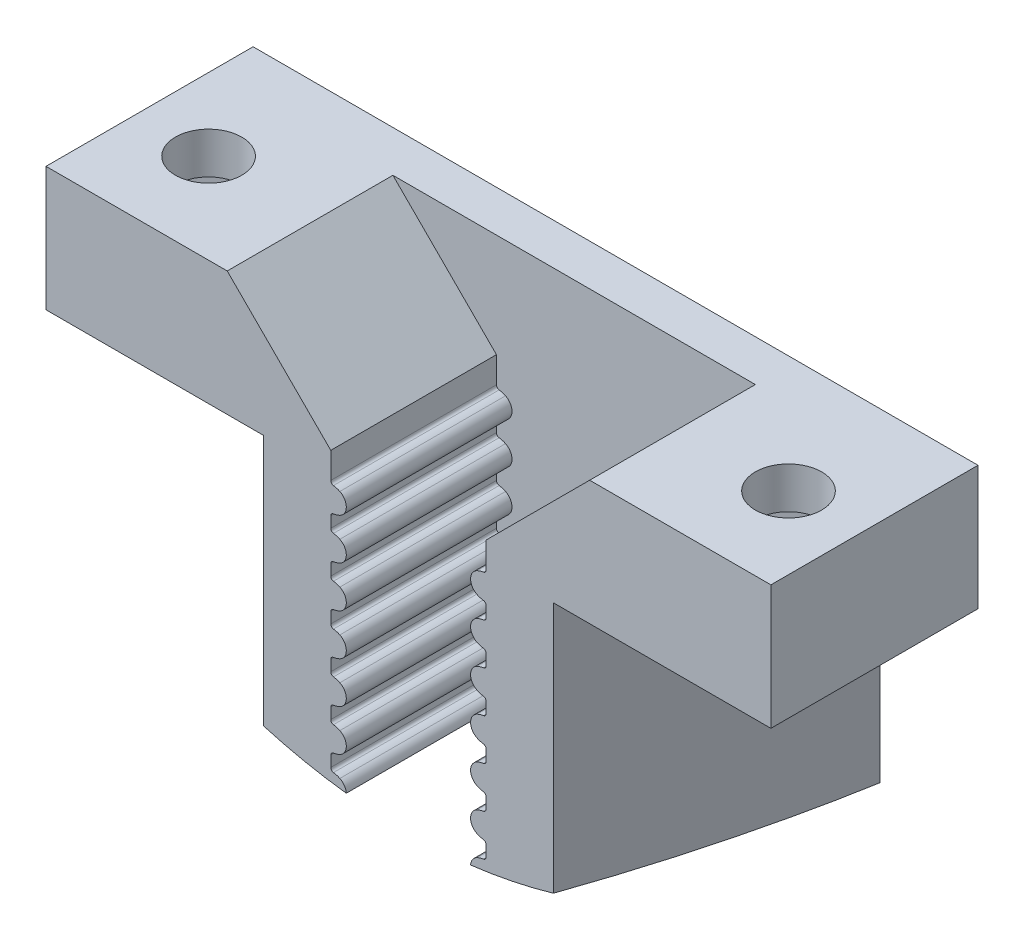
SolidWorks part; units mm, degrees
ref_plane "Front" through (0, 0, 0) normal (0, 0, 1) x (1, 0, 0)
ref_plane "Top" through (0, 0, 0) normal (0, 1, 0) x (1, 0, 0)
ref_plane "Right" through (0, 0, 0) normal (1, 0, 0) x (0, 0, -1)
sketch "Sketch1" plane through (0, 0, 0) normal (0, 0, 1) x (1, 0, 0)
  line L1 (-17.5, -3) -> (17.5, -3)
  line L2 (-17.5, -3) -> (-17.5, 3)
  line L3 (-17.5, 3) -> (17.5, 3)
  line L4 (17.5, -3) -> (17.5, 3)
  line L5 (-17.5, -3) -> (17.5, 3) construction
  line L6 (-17.5, 3) -> (17.5, -3) construction
  point P0 (0, 0)
  dimension "D1" = 35
  dimension "D2" = 6
extrude "Boss-Extrude1" add sketch "Sketch1" along normal blind 10
sketch "Sketch2" plane through (0, 0, 10) normal (0, 0, 1) x (1, 0, 0)
  line L0 (-17.5, -3) -> (17.5, -3) construction
  line L1 (-17.5, -3) -> (17.5, -3)
  arc A0 (-17.5, -3) -> (17.5, -3) centre (0, 14.8536) ccw
  dimension "D1" = 50
extrude "Boss-Extrude2" add sketch "Sketch2" against normal blind 10
sketch "Sketch4" plane through (0, 0, 10) normal (0, 0, 1) x (1, 0, 0)
  line L0 (17.5, 3) -> (-17.5, 3) construction
  line L1 (-3, 3) -> (3, 3)
  line L2 (-3, 3) -> (-3, -10.1464)
  line L3 (-3, -10.1464) -> (3, -10.1464)
  line L4 (3, 3) -> (3, -10.1464)
  arc A0 (-17.5, -3) -> (17.5, -3) centre (0, 14.8536) ccw construction
  point P10 (0, 3)
  dimension "D1" = 6
extrude "Cut-Extrude1" cut sketch "Sketch4" against normal blind 8
sketch "Sketch5" plane through (0, 0, 10) normal (0, 0, 1) x (1, 0, 0)
  line L0 (3, 2) -> (3.75, 2) construction
  line L1 (3, 4) -> (3.75, 4) construction
  line L2 (3, -9.9658) -> (3, 3) construction
  line L3 (3.75, 2.7402) -> (3, 2.7402) construction
  line L4 (3.75, 2.7402) -> (3.75, 2) construction
  line L5 (3.75, 3.2598) -> (3.75, 4) construction
  line L6 (3, 2) -> (3, 4)
  line L7 (17.5, 3) -> (3, 3) construction
  line L8 (3, -9.9658) -> (3, 3) construction
  line L9 (3.75, 3.2598) -> (3.75, 2.7402)
  arc A0 (3.3118, 2.4989) -> (3, 2) centre (3.555, 2) ccw
  arc A1 (3.6196, 2.5915) -> (3.3118, 2.4989) centre (3.75, 1.6) ccw
  arc A2 (3.6196, 2.5915) -> (3.75, 2.7402) centre (3.6, 2.7402) ccw
  arc A3 (3.3118, 3.5011) -> (3, 4) centre (3.555, 4) cw
  arc A4 (3.6196, 3.4085) -> (3.3118, 3.5011) centre (3.75, 4.4) cw
  arc A5 (3.6196, 3.4085) -> (3.75, 3.2598) centre (3.6, 3.2598) cw
  point P6 (3, 2)
  dimension "D4" = 1.11
  dimension "D7" = 0.3
  dimension "D8" = 1
  dimension "D1" = 0.6196
  dimension "D2" = 0.75
  dimension "D3" = 1
  dimension "D6" = 0.4
extrude "Cut-Extrude2" cut sketch "Sketch5" against normal blind 8
pattern_linear "LPattern2" count 10 spacing 2 along (0, -1, 0) of "Cut-Extrude2"
mirror "Mirror1" about plane through (0, 0, 0) normal (1, 0, 0) of "LPattern2", "Cut-Extrude2"
sketch "Sketch6" plane through (0, 3, 0) normal (0, 1, 0) x (1, 0, 0)
  line L0 (-17.5, 0) -> (-12.7735, 0)
  line L1 (17.5, 0) -> (-17.5, 0) construction
  line L2 (-12.7735, 0) -> (-7, -10)
  line L3 (-3.75, -10) -> (-17.5, -10) construction
  line L4 (-7, -10) -> (-17.5, -10)
  line L5 (-17.5, -10) -> (-17.5, 0)
  dimension "D1" = 60
  dimension "D2" = 10.5
extrude "Cut-Extrude3" cut sketch "Sketch6" against normal through all
mirror "Mirror2" about plane through (0, 0, 0) normal (1, 0, 0) of "Cut-Extrude3"
sketch "Sketch7" plane through (0, 3, 0) normal (0, 1, 0) x (1, 0, 0)
  line L0 (12.7735, 0) -> (-12.7735, 0) construction
  line L3 (-17.5, 0) -> (17.5, 0)
  line L4 (-17.5, 0) -> (-17.5, -10)
  line L5 (-17.5, -10) -> (17.5, -10)
  line L6 (17.5, 0) -> (17.5, -10)
  line L7 (-3.75, -10) -> (-7, -10) construction
  point P9 (0, 0)
  dimension "D1" = 35
extrude "Boss-Extrude3" add sketch "Sketch7" along normal blind 6
sketch "Sketch8" plane through (0, 0, 10) normal (0, 0, 1) x (1, 0, 0)
  line L0 (-17.5, 9) -> (17.5, 9) construction
  line L1 (-3.75, 3) -> (3.75, 3)
  line L2 (-3.75, 3) -> (-3.75, 9)
  line L3 (-3.75, 9) -> (3.75, 9)
  line L4 (3.75, 3) -> (3.75, 9)
extrude "Cut-Extrude4" cut sketch "Sketch8" against normal blind 8
sketch "Sketch9" plane through (0, 3, 0) normal (0, -1, 0) x (1, 0, 0)
  line L0 (7, 10) -> (17.5, 10) construction
  line L1 (16.8146, 4.025) -> (16.8146, 7.275)
  line L2 (16.8146, 7.275) -> (14, 8.9)
  line L3 (14, 8.9) -> (11.1854, 7.275)
  line L4 (11.1854, 7.275) -> (11.1854, 4.025)
  line L5 (11.1854, 4.025) -> (14, 2.4)
  line L6 (14, 2.4) -> (16.8146, 4.025)
  circle A0 centre (14, 5.65) radius 3.25 construction
  dimension "D1" = 6.5
  dimension "D2" = 4.35
  dimension "D3" = 14
extrude "Cut-Extrude5" cut sketch "Sketch9" against normal blind 4
mirror "Mirror3" about plane through (0, 0, 0) normal (1, 0, 0) of "Cut-Extrude5"
sketch "Sketch10" plane through (0, 7, 0) normal (0, -1, 0) x (1, 0, 0)
  circle A0 centre (14, 5.65) radius 1.6
  dimension "D1" = 3.2
extrude "Cut-Extrude6" cut sketch "Sketch10" against normal through all
mirror "Mirror4" about plane through (0, 0, 0) normal (1, 0, 0) of "Cut-Extrude6"
chamfer "Chamfer1" distance 5 angle 45 1 edges at (3.75, 9, 6)
